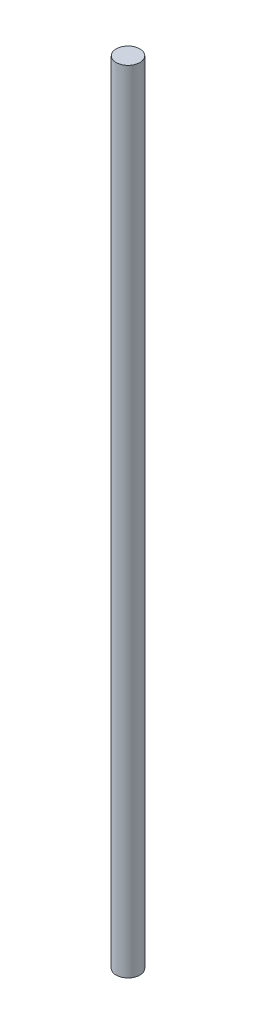
SolidWorks part; units mm, degrees
ref_plane "前视基准面" through (0, 0, 0) normal (0, 0, 1) x (1, 0, 0)
ref_plane "上视基准面" through (0, 0, 0) normal (0, 1, 0) x (1, 0, 0)
ref_plane "右视基准面" through (0, 0, 0) normal (1, 0, 0) x (0, 0, -1)
other "Configuration Table"
sketch "草图1" plane through (0, 0, 0) normal (0, 1, 0) x (1, 0, 0)
  circle A0 centre (0, 0) radius 1.5
  dimension "D1" = 3
extrude "凸台-拉伸1" add sketch "草图1" along normal blind 100
